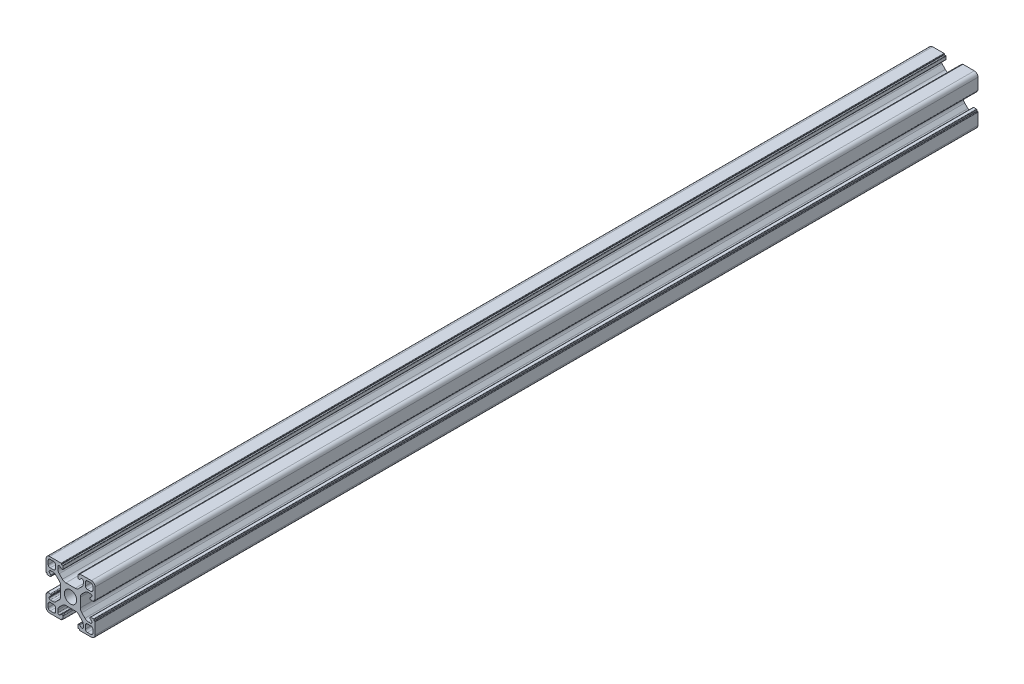
SolidWorks part; units mm, degrees
material "1060 Сплав"
ref_plane "Спереди" through (0, 0, 0) normal (0, 0, 1) x (1, 0, 0)
ref_plane "Сверху" through (0, 0, 0) normal (0, 1, 0) x (1, 0, 0)
ref_plane "Справа" through (0, 0, 0) normal (1, 0, 0) x (0, 0, -1)
sketch "Эскиз1" plane through (0, 0, 0) normal (0, 0, 1) x (1, 0, 0)
  line L0 (-22.0052, 70.3096) -> (-25.0052, 67.3096) construction
  line L1 (-31.1052, 65.2096) -> (-29.2064, 65.2096)
  line L2 (-31.1052, 61.2096) -> (-21.1052, 71.2096) construction
  line L3 (-23.5052, 68.8096) -> (-25.0052, 70.3096) construction
  line L4 (-27.7922, 65.7954) -> (-26.4909, 67.0967)
  line L5 (-24.2052, 67.3096) -> (-22.8052, 67.3096)
  line L6 (-25.0052, 68.1096) -> (-25.0052, 69.5096)
  line L7 (-22.8052, 70.3096) -> (-24.2052, 70.3096)
  line L8 (-25.9052, 69.4096) -> (-25.9052, 68.5109)
  line L9 (-27.3419, 69.2829) -> (-26.8616, 69.7632)
  line L10 (-27.9052, 70.7587) -> (-27.4052, 70.7587)
  line L11 (-27.5187, 69.2096) -> (-27.8052, 69.2096)
  line L12 (-26.508, 69.9096) -> (-26.4052, 69.9096)
  line L13 (-27.4052, 71.0596) -> (-27.4052, 70.7587)
  line L14 (-28.0552, 70.6087) -> (-28.0552, 69.4596)
  line L15 (-22.6052, 71.2096) -> (-27.2552, 71.2096)
  line L16 (-22.0052, 69.5096) -> (-22.0052, 68.1096)
  line L17 (-21.1052, 69.7096) -> (-21.1052, 65.0596)
  line L18 (-21.7061, 64.2596) -> (-22.8552, 64.2596)
  line L19 (-21.2552, 64.9096) -> (-21.5561, 64.9096)
  line L20 (-22.4052, 65.8068) -> (-22.4052, 65.9096)
  line L21 (-23.1052, 64.7961) -> (-23.1052, 64.5096)
  line L22 (-21.5561, 64.4096) -> (-21.5561, 64.9096)
  line L23 (-23.0319, 64.9729) -> (-22.5516, 65.4532)
  line L24 (-22.9052, 66.4096) -> (-23.8039, 66.4096)
  line L25 (-26.5194, 64.5226) -> (-25.2181, 65.8239)
  line L26 (-27.1052, 61.2096) -> (-27.1052, 63.1084)
  line L27 (-27.1052, 61.2096) -> (-27.1052, 59.3109)
  line L28 (-26.5194, 57.8967) -> (-25.2181, 56.5954)
  line L29 (-25.0052, 54.3096) -> (-25.0052, 52.9096)
  line L30 (-24.2052, 55.1096) -> (-22.8052, 55.1096)
  line L31 (-22.0052, 52.9096) -> (-22.0052, 54.3096)
  line L32 (-22.9052, 56.0096) -> (-23.8039, 56.0096)
  line L33 (-23.0319, 57.4464) -> (-22.5516, 56.9661)
  line L34 (-21.5561, 58.0096) -> (-21.5561, 57.5096)
  line L35 (-23.1052, 57.6232) -> (-23.1052, 57.9096)
  line L36 (-22.4052, 56.6125) -> (-22.4052, 56.5096)
  line L37 (-21.2552, 57.5096) -> (-21.5561, 57.5096)
  line L38 (-21.7061, 58.1596) -> (-22.8552, 58.1596)
  line L39 (-21.1052, 52.7096) -> (-21.1052, 57.3596)
  line L40 (-22.8052, 52.1096) -> (-24.2052, 52.1096)
  line L41 (-22.6052, 51.2096) -> (-27.2552, 51.2096)
  line L42 (-28.0552, 51.8106) -> (-28.0552, 52.9596)
  line L43 (-27.4052, 51.3596) -> (-27.4052, 51.6606)
  line L44 (-26.508, 52.5096) -> (-26.4052, 52.5096)
  line L45 (-27.5187, 53.2096) -> (-27.8052, 53.2096)
  line L46 (-27.9052, 51.6606) -> (-27.4052, 51.6606)
  line L47 (-27.3419, 53.1364) -> (-26.8616, 52.6561)
  line L48 (-25.9052, 53.0096) -> (-25.9052, 53.9084)
  line L49 (-27.7922, 56.6239) -> (-26.4909, 55.3226)
  line L50 (-31.1052, 57.2096) -> (-29.2064, 57.2096)
  line L51 (-22.0052, 52.1096) -> (-25.0052, 55.1096) construction
  line L52 (-31.1052, 61.2096) -> (-21.1052, 51.2096) construction
  line L53 (-23.5052, 53.6096) -> (-22.0052, 55.1096) construction
  line L54 (-31.1052, 57.2096) -> (-33.0039, 57.2096)
  line L55 (-34.4181, 56.6239) -> (-35.7194, 55.3226)
  line L56 (-38.0052, 55.1096) -> (-39.4052, 55.1096)
  line L57 (-37.2052, 54.3096) -> (-37.2052, 52.9096)
  line L58 (-39.4052, 52.1096) -> (-38.0052, 52.1096)
  line L59 (-36.3052, 53.0096) -> (-36.3052, 53.9084)
  line L60 (-34.8684, 53.1364) -> (-35.3487, 52.6561)
  line L61 (-34.3052, 51.6606) -> (-34.8052, 51.6606)
  line L62 (-34.6916, 53.2096) -> (-34.4052, 53.2096)
  line L63 (-35.7023, 52.5096) -> (-35.8052, 52.5096)
  line L64 (-34.8052, 51.3596) -> (-34.8052, 51.6606)
  line L65 (-34.1552, 51.8106) -> (-34.1552, 52.9596)
  line L66 (-39.6052, 51.2096) -> (-34.9552, 51.2096)
  line L67 (-40.2052, 52.9096) -> (-40.2052, 54.3096)
  line L68 (-41.1052, 52.7096) -> (-41.1052, 57.3596)
  line L69 (-40.5042, 58.1596) -> (-39.3552, 58.1596)
  line L70 (-40.9552, 57.5096) -> (-40.6542, 57.5096)
  line L71 (-39.8052, 56.6125) -> (-39.8052, 56.5096)
  line L72 (-39.1052, 57.6232) -> (-39.1052, 57.9096)
  line L73 (-40.6542, 58.0096) -> (-40.6542, 57.5096)
  line L74 (-39.1784, 57.4464) -> (-39.6587, 56.9661)
  line L75 (-39.3052, 56.0096) -> (-38.4064, 56.0096)
  line L76 (-35.6909, 57.8967) -> (-36.9922, 56.5954)
  line L77 (-35.1052, 61.2096) -> (-35.1052, 59.3109)
  line L78 (-40.2052, 52.1096) -> (-37.2052, 55.1096) construction
  line L79 (-31.1052, 61.2096) -> (-41.1052, 51.2096) construction
  line L80 (-38.7052, 53.6096) -> (-37.2052, 52.1096) construction
  line L81 (-35.1052, 61.2096) -> (-35.1052, 63.1084)
  line L82 (-35.6909, 64.5226) -> (-36.9922, 65.8239)
  line L83 (-37.2052, 68.1096) -> (-37.2052, 69.5096)
  line L84 (-38.0052, 67.3096) -> (-39.4052, 67.3096)
  line L85 (-40.2052, 69.5096) -> (-40.2052, 68.1096)
  line L86 (-39.3052, 66.4096) -> (-38.4064, 66.4096)
  line L87 (-39.1784, 64.9729) -> (-39.6587, 65.4532)
  line L88 (-40.6542, 64.4096) -> (-40.6542, 64.9096)
  line L89 (-39.1052, 64.7961) -> (-39.1052, 64.5096)
  line L90 (-39.8052, 65.8068) -> (-39.8052, 65.9096)
  line L91 (-40.9552, 64.9096) -> (-40.6542, 64.9096)
  line L92 (-40.5042, 64.2596) -> (-39.3552, 64.2596)
  line L93 (-41.1052, 69.7096) -> (-41.1052, 65.0596)
  line L94 (-39.4052, 70.3096) -> (-38.0052, 70.3096)
  line L95 (-39.6052, 71.2096) -> (-34.9552, 71.2096)
  line L96 (-34.1552, 70.6087) -> (-34.1552, 69.4596)
  line L97 (-34.8052, 71.0596) -> (-34.8052, 70.7587)
  line L98 (-35.7023, 69.9096) -> (-35.8052, 69.9096)
  line L99 (-34.6916, 69.2096) -> (-34.4052, 69.2096)
  line L100 (-34.3052, 70.7587) -> (-34.8052, 70.7587)
  line L101 (-34.8684, 69.2829) -> (-35.3487, 69.7632)
  line L102 (-36.3052, 69.4096) -> (-36.3052, 68.5109)
  line L103 (-34.4181, 65.7954) -> (-35.7194, 67.0967)
  line L104 (-31.1052, 65.2096) -> (-33.0039, 65.2096)
  line L105 (-42.8692, 61.2096) -> (-19.6008, 61.2096) construction
  line L106 (-40.2052, 70.3096) -> (-37.2052, 67.3096) construction
  line L107 (-31.1052, 49.1232) -> (-31.1052, 71.9286) construction
  line L108 (-31.1052, 61.2096) -> (-41.1052, 71.2096) construction
  line L109 (-38.7052, 68.8096) -> (-40.2052, 67.3096) construction
  arc A0 (-22.0052, 69.5096) -> (-22.8052, 70.3096) centre (-22.8052, 69.5096) ccw
  arc A1 (-24.2052, 70.3096) -> (-25.0052, 69.5096) centre (-24.2052, 69.5096) ccw
  arc A2 (-24.2052, 67.3096) -> (-25.0052, 68.1096) centre (-24.2052, 68.1096) cw
  arc A3 (-22.6052, 71.2096) -> (-21.1052, 69.7096) centre (-22.6052, 69.7096) cw
  arc A4 (-27.9052, 70.7587) -> (-28.0552, 70.6087) centre (-27.9052, 70.6087) ccw
  arc A5 (-27.2552, 71.2096) -> (-27.4052, 71.0596) centre (-27.2552, 71.0596) ccw
  arc A6 (-27.5187, 69.2096) -> (-27.3419, 69.2829) centre (-27.5187, 69.4596) ccw
  arc A7 (-27.8052, 69.2096) -> (-28.0552, 69.4596) centre (-27.8052, 69.4596) cw
  arc A8 (-26.8616, 69.7632) -> (-26.508, 69.9096) centre (-26.508, 69.4096) cw
  arc A9 (-26.4052, 69.9096) -> (-25.9052, 69.4096) centre (-26.4052, 69.4096) cw
  arc A10 (-28.6052, 61.2096) -> (-31.1052, 63.7096) centre (-31.1052, 61.2096) ccw
  arc A11 (-29.2064, 65.2096) -> (-27.7922, 65.7954) centre (-29.2064, 67.2096) ccw
  arc A12 (-25.9052, 68.5109) -> (-26.4909, 67.0967) centre (-27.9052, 68.5109) cw
  arc A13 (-22.0052, 68.1096) -> (-22.8052, 67.3096) centre (-22.8052, 68.1096) cw
  arc A14 (-22.4052, 65.9096) -> (-22.9052, 66.4096) centre (-22.9052, 65.9096) ccw
  arc A15 (-22.5516, 65.4532) -> (-22.4052, 65.8068) centre (-22.9052, 65.8068) ccw
  arc A16 (-23.1052, 64.5096) -> (-22.8552, 64.2596) centre (-22.8552, 64.5096) ccw
  arc A17 (-23.1052, 64.7961) -> (-23.0319, 64.9729) centre (-22.8552, 64.7961) cw
  arc A18 (-21.1052, 65.0596) -> (-21.2552, 64.9096) centre (-21.2552, 65.0596) cw
  arc A19 (-21.5561, 64.4096) -> (-21.7061, 64.2596) centre (-21.7061, 64.4096) cw
  arc A20 (-23.8039, 66.4096) -> (-25.2181, 65.8239) centre (-23.8039, 64.4096) ccw
  arc A21 (-27.1052, 63.1084) -> (-26.5194, 64.5226) centre (-25.1052, 63.1084) cw
  arc A22 (-22.8052, 52.1096) -> (-22.0052, 52.9096) centre (-22.8052, 52.9096) ccw
  arc A23 (-22.0052, 54.3096) -> (-22.8052, 55.1096) centre (-22.8052, 54.3096) ccw
  arc A24 (-25.0052, 54.3096) -> (-24.2052, 55.1096) centre (-24.2052, 54.3096) cw
  arc A25 (-21.1052, 52.7096) -> (-22.6052, 51.2096) centre (-22.6052, 52.7096) cw
  arc A26 (-21.5561, 58.0096) -> (-21.7061, 58.1596) centre (-21.7061, 58.0096) ccw
  arc A27 (-21.1052, 57.3596) -> (-21.2552, 57.5096) centre (-21.2552, 57.3596) ccw
  arc A28 (-23.1052, 57.6232) -> (-23.0319, 57.4464) centre (-22.8552, 57.6232) ccw
  arc A29 (-23.1052, 57.9096) -> (-22.8552, 58.1596) centre (-22.8552, 57.9096) cw
  arc A30 (-22.5516, 56.9661) -> (-22.4052, 56.6125) centre (-22.9052, 56.6125) cw
  arc A31 (-22.4052, 56.5096) -> (-22.9052, 56.0096) centre (-22.9052, 56.5096) cw
  arc A32 (-31.1052, 58.7096) -> (-28.6052, 61.2096) centre (-31.1052, 61.2096) ccw
  arc A33 (-27.1052, 59.3109) -> (-26.5194, 57.8967) centre (-25.1052, 59.3109) ccw
  arc A34 (-23.8039, 56.0096) -> (-25.2181, 56.5954) centre (-23.8039, 58.0096) cw
  arc A35 (-24.2052, 52.1096) -> (-25.0052, 52.9096) centre (-24.2052, 52.9096) cw
  arc A36 (-26.4052, 52.5096) -> (-25.9052, 53.0096) centre (-26.4052, 53.0096) ccw
  arc A37 (-26.8616, 52.6561) -> (-26.508, 52.5096) centre (-26.508, 53.0096) ccw
  arc A38 (-27.8052, 53.2096) -> (-28.0552, 52.9596) centre (-27.8052, 52.9596) ccw
  arc A39 (-27.5187, 53.2096) -> (-27.3419, 53.1364) centre (-27.5187, 52.9596) cw
  arc A40 (-27.2552, 51.2096) -> (-27.4052, 51.3596) centre (-27.2552, 51.3596) cw
  arc A41 (-27.9052, 51.6606) -> (-28.0552, 51.8106) centre (-27.9052, 51.8106) cw
  arc A42 (-25.9052, 53.9084) -> (-26.4909, 55.3226) centre (-27.9052, 53.9084) ccw
  arc A43 (-29.2064, 57.2096) -> (-27.7922, 56.6239) centre (-29.2064, 55.2096) cw
  arc A44 (-40.2052, 52.9096) -> (-39.4052, 52.1096) centre (-39.4052, 52.9096) ccw
  arc A45 (-38.0052, 52.1096) -> (-37.2052, 52.9096) centre (-38.0052, 52.9096) ccw
  arc A46 (-38.0052, 55.1096) -> (-37.2052, 54.3096) centre (-38.0052, 54.3096) cw
  arc A47 (-39.6052, 51.2096) -> (-41.1052, 52.7096) centre (-39.6052, 52.7096) cw
  arc A48 (-34.3052, 51.6606) -> (-34.1552, 51.8106) centre (-34.3052, 51.8106) ccw
  arc A49 (-34.9552, 51.2096) -> (-34.8052, 51.3596) centre (-34.9552, 51.3596) ccw
  arc A50 (-34.6916, 53.2096) -> (-34.8684, 53.1364) centre (-34.6916, 52.9596) ccw
  arc A51 (-34.4052, 53.2096) -> (-34.1552, 52.9596) centre (-34.4052, 52.9596) cw
  arc A52 (-35.3487, 52.6561) -> (-35.7023, 52.5096) centre (-35.7023, 53.0096) cw
  arc A53 (-35.8052, 52.5096) -> (-36.3052, 53.0096) centre (-35.8052, 53.0096) cw
  arc A54 (-33.6052, 61.2096) -> (-31.1052, 58.7096) centre (-31.1052, 61.2096) ccw
  arc A55 (-33.0039, 57.2096) -> (-34.4181, 56.6239) centre (-33.0039, 55.2096) ccw
  arc A56 (-36.3052, 53.9084) -> (-35.7194, 55.3226) centre (-34.3052, 53.9084) cw
  arc A57 (-40.2052, 54.3096) -> (-39.4052, 55.1096) centre (-39.4052, 54.3096) cw
  arc A58 (-39.8052, 56.5096) -> (-39.3052, 56.0096) centre (-39.3052, 56.5096) ccw
  arc A59 (-39.6587, 56.9661) -> (-39.8052, 56.6125) centre (-39.3052, 56.6125) ccw
  arc A60 (-39.1052, 57.9096) -> (-39.3552, 58.1596) centre (-39.3552, 57.9096) ccw
  arc A61 (-39.1052, 57.6232) -> (-39.1784, 57.4464) centre (-39.3552, 57.6232) cw
  arc A62 (-41.1052, 57.3596) -> (-40.9552, 57.5096) centre (-40.9552, 57.3596) cw
  arc A63 (-40.6542, 58.0096) -> (-40.5042, 58.1596) centre (-40.5042, 58.0096) cw
  arc A64 (-38.4064, 56.0096) -> (-36.9922, 56.5954) centre (-38.4064, 58.0096) ccw
  arc A65 (-35.1052, 59.3109) -> (-35.6909, 57.8967) centre (-37.1052, 59.3109) cw
  arc A66 (-39.4052, 70.3096) -> (-40.2052, 69.5096) centre (-39.4052, 69.5096) ccw
  arc A67 (-40.2052, 68.1096) -> (-39.4052, 67.3096) centre (-39.4052, 68.1096) ccw
  arc A68 (-37.2052, 68.1096) -> (-38.0052, 67.3096) centre (-38.0052, 68.1096) cw
  arc A69 (-41.1052, 69.7096) -> (-39.6052, 71.2096) centre (-39.6052, 69.7096) cw
  arc A70 (-40.6542, 64.4096) -> (-40.5042, 64.2596) centre (-40.5042, 64.4096) ccw
  arc A71 (-41.1052, 65.0596) -> (-40.9552, 64.9096) centre (-40.9552, 65.0596) ccw
  arc A72 (-39.1052, 64.7961) -> (-39.1784, 64.9729) centre (-39.3552, 64.7961) ccw
  arc A73 (-39.1052, 64.5096) -> (-39.3552, 64.2596) centre (-39.3552, 64.5096) cw
  arc A74 (-39.6587, 65.4532) -> (-39.8052, 65.8068) centre (-39.3052, 65.8068) cw
  arc A75 (-39.8052, 65.9096) -> (-39.3052, 66.4096) centre (-39.3052, 65.9096) cw
  arc A76 (-31.1052, 63.7096) -> (-33.6052, 61.2096) centre (-31.1052, 61.2096) ccw
  arc A77 (-35.1052, 63.1084) -> (-35.6909, 64.5226) centre (-37.1052, 63.1084) ccw
  arc A78 (-38.4064, 66.4096) -> (-36.9922, 65.8239) centre (-38.4064, 64.4096) cw
  arc A79 (-38.0052, 70.3096) -> (-37.2052, 69.5096) centre (-38.0052, 69.5096) cw
  arc A80 (-35.8052, 69.9096) -> (-36.3052, 69.4096) centre (-35.8052, 69.4096) ccw
  arc A81 (-35.3487, 69.7632) -> (-35.7023, 69.9096) centre (-35.7023, 69.4096) ccw
  arc A82 (-34.4052, 69.2096) -> (-34.1552, 69.4596) centre (-34.4052, 69.4596) ccw
  arc A83 (-34.6916, 69.2096) -> (-34.8684, 69.2829) centre (-34.6916, 69.4596) cw
  arc A84 (-34.9552, 71.2096) -> (-34.8052, 71.0596) centre (-34.9552, 71.0596) cw
  arc A85 (-34.3052, 70.7587) -> (-34.1552, 70.6087) centre (-34.3052, 70.6087) cw
  arc A86 (-36.3052, 68.5109) -> (-35.7194, 67.0967) centre (-34.3052, 68.5109) ccw
  arc A87 (-33.0039, 65.2096) -> (-34.4181, 65.7954) centre (-33.0039, 67.2096) cw
  point P0 (-31.1052, 61.2096)
  point P9 (-31.1052, 61.2096)
  point P40 (-22.4052, 64.9096)
  point P93 (-27.4052, 52.5096)
  point P144 (-27.4052, 69.9096)
  point P152 (-22.4052, 57.5096)
  point P153 (-31.1052, 57.2854)
  point P154 (-31.1052, 61.2096)
  point P189 (-39.8052, 57.5096)
  point P228 (-34.8052, 52.5096)
  point P229 (-35.0294, 61.2096)
  point P230 (-31.1052, 61.2096)
  point P268 (-34.8052, 69.9096)
  point P273 (-27.1809, 61.2096)
  point P306 (-39.8052, 64.9096)
  point P307 (-31.1052, 65.1339)
  point P309 (-31.1052, 61.2096)
  dimension "D3" = 5
  dimension "D6" = 2
  dimension "D1" = 2
  dimension "D2" = 6
  dimension "D4" = 4
  dimension "D5" = 0.9
extrude "Бобышка-Вытянуть1" add sketch "Эскиз1" along normal blind 360
